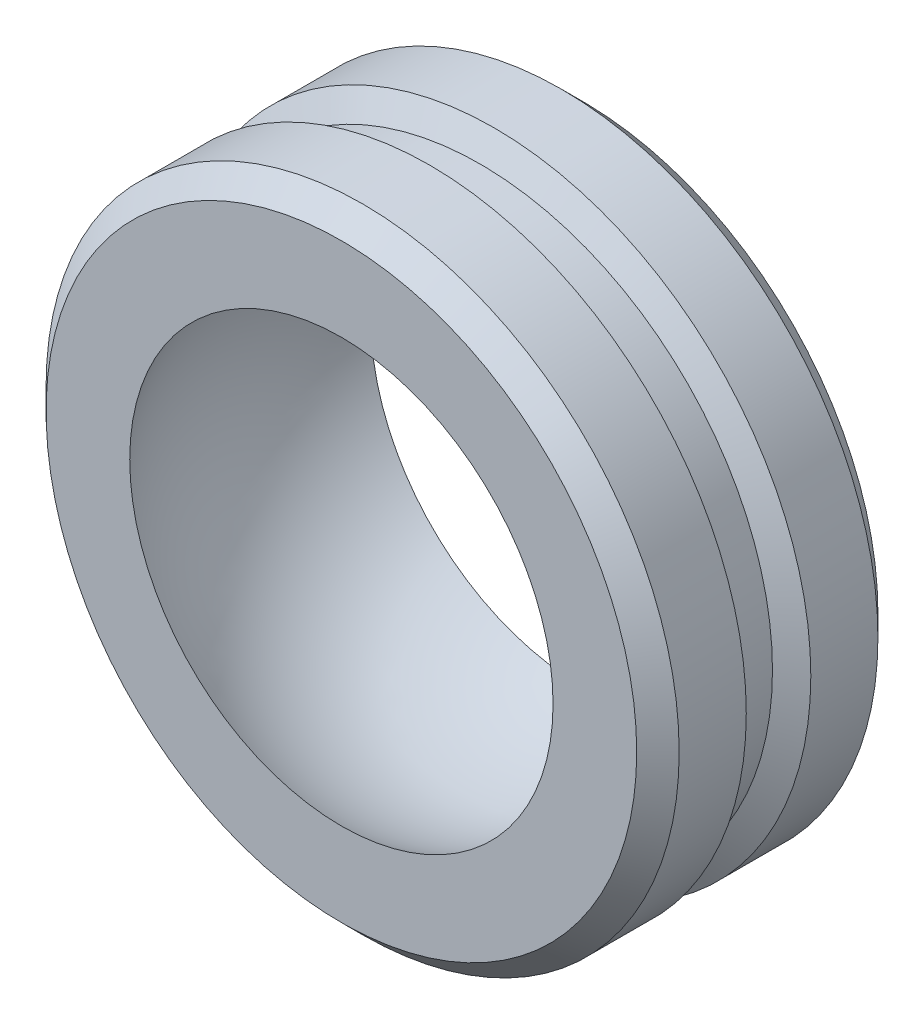
SolidWorks part; units mm, degrees
ref_plane "Front" through (0, 0, 0) normal (0, 0, 1) x (1, 0, 0)
ref_plane "Top" through (0, 0, 0) normal (0, 1, 0) x (1, 0, 0)
ref_plane "Right" through (0, 0, 0) normal (1, 0, 0) x (0, 0, -1)
sketch "Sketch1" plane through (0, 0, 0) normal (0, 0, 1) x (1, 0, 0)
  circle A0 centre (0, 0) radius 3.175 construction
  circle A1 centre (0, 0) radius 6.35 construction
  circle A2 centre (0, 0) radius 6.4135 construction
  circle A3 centre (0, 0) radius 8.3337
  dimension "D1" = 12.827
  dimension "D OD" = 16.6675
  dimension "B Hole Dia" = 6.35
  dimension "Ball Dia" = 12.7
extrude "Extrude1" add sketch "Sketch1" along normal mid plane 6.35
sketch "Sketch2" plane through (0, 0, 0) normal (0, 0, 1) x (1, 0, 0)
  line L0 (0, 6.4135) -> (0, -6.4135)
  line L1 (0, 6.4135) -> (0, 8.3337) construction
  circle A0 centre (0, 0) radius 6.4135 construction
  arc A1 (0, -6.4135) -> (0, 6.4135) centre (0, 0) ccw
  circle A2 centre (0, 0) radius 8.3337 construction
revolve "Cut-Revolve1" cut sketch "Sketch2" angle 360 about L1
sketch "Sketch3" plane through (0, 0, 0) normal (0, 0, 1) x (1, 0, 0)
  line L0 (0, 6.35) -> (0, -6.35)
  line L1 (0, 6.35) -> (0, 8.3337) construction
  circle A0 centre (0, 0) radius 6.35 construction
  arc A1 (0, -6.35) -> (0, 6.35) centre (0, 0) ccw
  circle A2 centre (0, 0) radius 8.3337 construction
revolve "Revolve1" add sketch "Sketch3" angle 360 about L1
sketch "Sketch4" plane through (0, 0, 0) normal (0, 0, 1) x (1, 0, 0)
  circle A0 centre (0, 0) radius 3.175 construction
  circle A1 centre (0, 0) radius 3.175
extrude "Cut-Extrude1" cut sketch "Sketch4" against normal through all and the other way through all
sketch "Sketch5" plane through (0, 0, 0) normal (1, 0, 0) x (0, 0, -1)
  line L0 (-4.3561, 8.3337) -> (4.3561, 8.3337) construction
  line L1 (-4.3561, 8.3337) -> (-5.4993, 8.3337)
  line L2 (-4.3561, 8.3337) -> (-4.3561, -8.3337)
  line L3 (-4.3561, -8.3337) -> (-5.4993, -8.3337)
  line L4 (-5.4993, 8.3337) -> (-5.4993, -8.3337)
  line L5 (4.3561, -8.3337) -> (5.4993, -8.3337)
  line L6 (4.3561, -8.3337) -> (4.3561, 8.3337)
  line L7 (4.3561, 8.3337) -> (5.4993, 8.3337)
  line L8 (5.4993, -8.3337) -> (5.4993, 8.3337)
  line L16 (3.175, 8.3337) -> (-3.175, 8.3337) construction
  line L17 (5.4993, -3.175) -> (5.4993, 3.175) construction
  line L18 (-5.4993, -3.175) -> (-5.4993, 3.175) construction
  line L19 (-4.3561, -8.3337) -> (4.3561, -8.3337) construction
  line L20 (-3.175, -8.3337) -> (3.175, -8.3337) construction
  line L21 (0, 0) -> (-4.3561, 1.0458) construction
  line L22 (0, 0) -> (-4.3561, -1.0458) construction
  dimension "W ball Width" = 8.7122
  dimension "Mis Angle" = 27
extrude "Cut-Extrude2" cut sketch "Sketch5" against normal through all and the other way through all
chamfer "Chamfer1" distance 0.5588 angle 45 2 edges at (8.3337, 0, 3.175) (8.3337, 0, -3.175)
sketch "Sketch7" plane through (0, 0, 0) normal (1, 0, 0) x (0, 0, -1)
  line L0 (0, 0) -> (-4.3561, -1.0458) construction
  line L1 (0, 0) -> (-4.3561, 1.0458) construction
  line L2 (0, 0) -> (-4.3561, -1.0458) construction
  line L3 (0, 0) -> (-4.3561, 1.0458) construction
sketch "Sketch8" plane through (0, 0, 0) normal (1, 0, 0) x (0, 0, -1)
  line L0 (-0.8496, 8.3337) -> (-0.4801, 7.6937)
  line L1 (-0.4801, 7.6937) -> (0.4801, 7.6937)
  line L2 (0.4801, 7.6937) -> (0.8496, 8.3337)
  line L3 (-0.8496, 8.3337) -> (0.8496, 8.3337)
  line L4 (2.6162, 8.3337) -> (-2.6162, 8.3337) construction
  line L5 (0, 0) -> (0, 7.6937) construction
  line L6 (0, 0) -> (4.3561, 0) construction
  line L7 (4.3561, -4.6203) -> (4.3561, 4.6203) construction
  line L8 (0, 6.4135) -> (0, 8.3337) construction
  arc A0 (3.175, 5.5725) -> (-3.175, 5.5725) centre (0, 0) ccw construction
  dimension "D1" = 60
  dimension "D2" = 1.9202
  dimension "D3" = 0.6401
  dimension "D4" = 0.9601
revolve "Cut-Revolve2" cut sketch "Sketch8" angle 360 about L6
delete or keep bodies "Body-Delete/Keep 1" type delete bodies bodies 112
ref_point "Point1"
equation "\"D1@Sketch1\"=\"Ball Dia@Sketch1\"*1.01"
equation "\"D3@Sketch8\" = \"D2@Sketch8\"/3"
equation "\"D4@Sketch8\" = \"D3@Sketch8\"*1.5"
